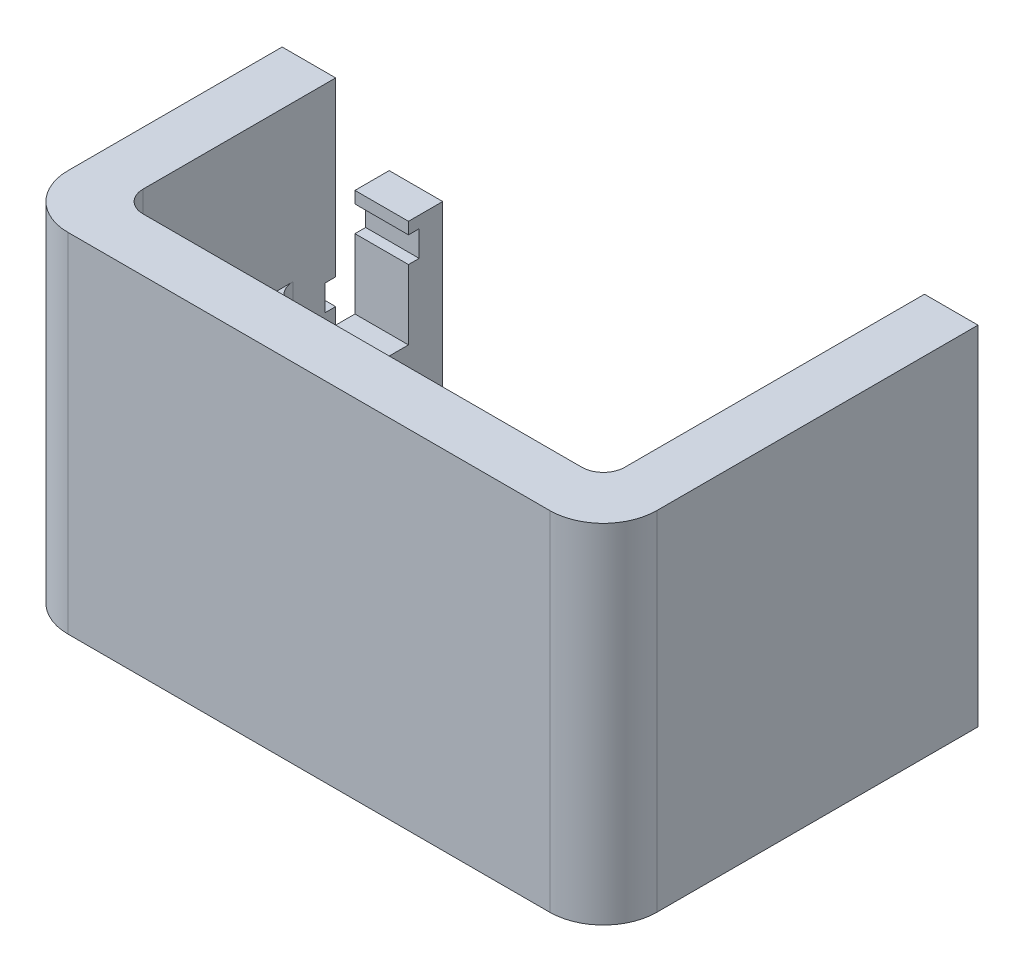
SolidWorks part; units mm, degrees
ref_plane "Front Plane" through (0, 0, 0) normal (0, 0, 1) x (1, 0, 0)
ref_plane "Top Plane" through (0, 0, 0) normal (0, 1, 0) x (1, 0, 0)
ref_plane "Right Plane" through (0, 0, 0) normal (1, 0, 0) x (0, 0, -1)
sketch "Sketch1" plane through (0, 0, 0) normal (0, 1, 0) x (1, 0, 0)
  line L0 (0, -55) -> (0, 55) construction
  line L1 (-34.925, -15.875) -> (34.925, -15.875)
  line L2 (-34.925, -15.875) -> (-34.925, 15.875)
  line L3 (-34.925, 15.875) -> (34.925, 15.875) construction
  line L4 (34.925, -15.875) -> (34.925, 15.875)
  line L5 (-34.925, -15.875) -> (34.925, 15.875) construction
  line L6 (-34.925, 15.875) -> (34.925, -15.875) construction
  line L7 (28.575, 15.875) -> (-28.575, 15.875) construction
  line L8 (28.575, 15.875) -> (28.575, -9.525)
  line L9 (28.575, -9.525) -> (-28.575, -9.525)
  line L10 (-28.575, 15.875) -> (-28.575, -9.525)
  line L11 (28.575, 15.875) -> (-28.575, -9.525) construction
  line L12 (28.575, -9.525) -> (-28.575, 15.875) construction
  line L13 (-28.575, 15.875) -> (-34.925, 15.875)
  line L14 (34.925, 15.875) -> (34.925, 28.575)
  line L15 (34.925, 28.575) -> (28.575, 28.575)
  line L16 (28.575, 28.575) -> (28.575, 15.875)
  point P0 (0, 0)
  point P6 (0, 3.175)
  point P11 (0, -9.525)
  dimension "D1" = 31.75
  dimension "D2" = 69.85
  dimension "D3" = 57.15
  dimension "D4" = 25.4
  dimension "D5" = 44.45
extrude "Boss-Extrude1" add sketch "Sketch1" along normal blind 38.1 contours L10 L3 L2 L1 L4 L8 L9
sketch "Sketch5" plane through (-28.575, 0, 0) normal (1, 0, 0) x (0, 0, -1)
  line L0 (15.875, 0) -> (-9.525, 0) construction
  line L1 (0.635, 16.51) -> (8.255, 16.51)
  line L2 (0.635, 16.51) -> (0.635, 19.685)
  line L3 (0.635, 19.685) -> (8.255, 19.685)
  line L4 (8.255, 16.51) -> (8.255, 19.685)
  line L5 (0.635, 16.51) -> (8.255, 19.685) construction
  line L6 (0.635, 19.685) -> (8.255, 16.51) construction
  line L10 (15.875, 38.1) -> (15.875, 0) construction
  point P0 (4.445, 18.0975)
  dimension "D1" = 7.62
  dimension "D2" = 3.175
  dimension "D3" = 16.51
  dimension "D4" = 7.62
extrude "Boss-Extrude2" add sketch "Sketch5" along normal blind 10.16 contours L3 L4 L1 L2
sketch "Sketch7" plane through (0, 19.685, 0) normal (0, 1, 0) x (1, 0, 0)
  line L1 (-28.575, 0.635) -> (-28.575, 8.255) construction
  line L3 (-18.415, 0.635) -> (-28.575, 0.635) construction
  point P0 (-23.241, 4.445)
  dimension "D1" = 3.81
  dimension "D2" = 5.334
hole_wizard "#6 Clearance Hole1" positions "Sketch8" profile "Sketch10" hole size "#6" standard "ANSI Inch" end condition up to next
sketch "Sketch8" plane through (0, 19.685, 0) normal (0, 1, 0) x (1, 0, 0)
  point P0 (-23.241, 4.445)
sketch "Sketch10" plane through (-23.241, 19.685, -4.445) normal (1, 0, 0) x (0, 0, 1)
  line L0 (0, 0) -> (0, 3.175)
  line L1 (0, 3.175) -> (1.8986, 3.175)
  line L2 (1.8986, 3.175) -> (1.8986, 0)
  line L5 (1.8986, 0) -> (0, 0)
  line L11 (0, -6.35) -> (0, 107.95) construction
  dimension "Thru Hole Dia." = 3.7973
  dimension "Thru Hole Depth" = 3.175
mirror "Mirror4" about plane through (0, 0, 0) normal (1, 0, 0) of "#6 Clearance Hole1", "Boss-Extrude2"
sketch "Sketch11" plane through (0, 0, 0) normal (0, -1, 0) x (1, 0, 0)
  line L5 (-28.575, -15.875) -> (-28.575, 9.525) construction
  line L7 (-34.925, 15.875) -> (-34.925, -15.875) construction
  line L13 (-28.575, -28.575) -> (-28.575, 9.525)
  line L15 (-34.925, 15.875) -> (-34.925, -28.575)
  line L17 (-34.925, -28.575) -> (-28.575, -28.575)
  line L18 (-28.575, -15.875) -> (-34.925, -15.875) construction
  line L19 (-28.575, 9.525) -> (28.575, 9.525)
  line L20 (28.575, 9.525) -> (28.575, -28.575)
  line L21 (28.575, -28.575) -> (34.925, -28.575)
  line L22 (34.925, -28.575) -> (34.925, 15.875)
  line L23 (34.925, 15.875) -> (-34.925, 15.875)
  dimension "D1" = 12.7
extrude "Boss-Extrude3" add sketch "Sketch11" along normal blind 3.175 contours L15 L17 L13 L19 L20 L21 L22 L23
sketch "Sketch12" [suppressed] plane through (0, 0, 0) normal (0, 1, 0) x (1, 0, 0)
  line L0 (-28.575, 28.575) -> (-28.575, 15.875) construction
  line L1 (-34.925, 28.575) -> (-28.575, 28.575)
  line L2 (-34.925, 28.575) -> (-34.925, 24.511)
  line L3 (-34.925, 24.511) -> (-28.575, 24.511)
  line L4 (-28.575, 28.575) -> (-28.575, 24.511)
  dimension "D1" = 4.064
extrude "Boss-Extrude4" [suppressed] add sketch "Sketch12" along normal blind 12.7
fillet "Fillet1" radius 6.35 2 edges at (34.925, 17.4625, 15.875) (-34.925, 17.4625, 15.875)
fillet "Fillet2" radius 2.54 4 edges at (-28.575, 18.0975, -0.635) (-28.575, 18.0975, -8.255) (28.575, 18.0975, -0.635) (28.575, 18.0975, -8.255)
fillet "Fillet3" radius 2.54 2 edges at (-28.575, 16.51, -4.445) (28.575, 16.51, -4.445)
fillet "Fillet4" radius 2.54 2 edges at (-28.575, 17.4625, 9.525) (28.575, 17.4625, 9.525)
sketch "Sketch13" [suppressed] plane through (0, 38.1, 0) normal (0, 1, 0) x (1, 0, 0)
  line L0 (28.575, 28.575) -> (28.575, -6.985) construction
  line L1 (34.925, 28.575) -> (28.575, 28.575) construction
  line L2 (26.035, -9.525) -> (-26.035, -9.525) construction
  line L3 (29.845, -11.43) -> (-29.845, -11.43) construction
  line L4 (0, -55) -> (0, 55) construction
  line L5 (-28.575, 28.575) -> (-34.925, 28.575) construction
  line L6 (-28.575, 15.875) -> (-34.925, 15.875) construction
  point P0 (29.845, -11.43)
  point P1 (-29.845, -11.43)
  point P2 (0, -11.43)
  point P7 (31.75, 24.765)
  point P12 (-31.75, 12.065)
  point P15 (31.75, 28.575)
  point P18 (-31.75, 28.575)
  dimension "D1" = 1.27
  dimension "D2" = 3.81
  dimension "D3" = 1.905
  dimension "D4" = 3.81
hole_wizard "#6-40 Tapped Hole1" [suppressed] positions "Sketch14" profile "Sketch16" tap size "#6-40" standard "ANSI Inch"
sketch "Sketch14" [suppressed] plane through (0, 38.1, 0) normal (0, 1, 0) x (1, 0, 0)
  point P0 (29.845, -11.43)
  point P3 (-29.845, -11.43)
  point P6 (31.75, 24.765)
  point P9 (-31.75, 12.065)
cosmetic thread "Hole Thread1" [suppressed] parameters "D1"=35.052, "D2"=3.5052
cosmetic thread "Hole Thread2" [suppressed] parameters "D1"=35.052, "D2"=3.5052
sketch "Sketch16" plane through (29.845, 38.1, 11.43) normal (1, 0, 0) x (0, 0, 1)
  line L0 (0, 0) -> (0, 38.9623)
  line L1 (0, 38.9623) -> (1.4351, 38.1)
  line L2 (1.4351, 38.1) -> (1.4351, 0)
  line L5 (1.4351, 0) -> (0, 0)
  line L10 (0, 38.9623) -> (-1.4351, 38.1) construction
  line L11 (0, -6.35) -> (0, 107.95) construction
  dimension "Tap Drill Dia." = 2.8702
  dimension "Tap Drill Depth" = 38.1
  dimension "Drill Angle" = 118
cosmetic thread "Hole Thread3" [suppressed] parameters "D1"=35.052, "D2"=3.5052
cosmetic thread "Hole Thread4" [suppressed] parameters "D1"=35.052, "D2"=3.5052
sketch "Sketch17" [suppressed] plane through (-34.925, 0, 0) normal (-1, 0, 0) x (0, 0, 1)
  line L0 (-28.575, 0) -> (-28.575, 31.75)
  line L1 (-28.575, 31.75) -> (-15.875, 31.75)
  line L2 (24.4475, 0) -> (-24.4475, 0) construction
  line L3 (-28.575, 0) -> (-24.511, 0)
  line L4 (-24.511, 0) -> (-24.511, 27.686)
  line L5 (-24.511, 27.686) -> (-15.875, 27.686)
  line L6 (-15.875, 31.75) -> (-15.875, 0) construction
  line L7 (-15.875, 27.686) -> (-15.875, 31.75)
  dimension "D1" = 4.064
  dimension "D2" = 4.064
extrude "Boss-Extrude5" [suppressed] add sketch "Sketch17" against normal up to surface (6.35 mm away)
sketch "Sketch18" plane through (-34.925, 0, 0) normal (-1, 0, 0) x (0, 0, 1)
  line L0 (-24.511, 19.05) -> (-28.575, 19.05)
  line L1 (-28.575, 38.1) -> (-28.575, -3.175) construction
  line L2 (-28.575, 19.05) -> (-24.511, 19.05) construction
  line L3 (-28.575, 19.05) -> (-28.575, 0)
  line L4 (-28.575, 0) -> (-15.875, 0)
  line L5 (-15.875, 0) -> (-15.875, 6.35)
  line L6 (-15.875, 38.1) -> (-15.875, 0) construction
  line L7 (-15.875, 6.35) -> (-24.511, 6.35)
  line L8 (-24.511, 22.7511) -> (-24.511, 6.858) construction
  line L9 (-24.511, 6.35) -> (-24.511, 19.05)
  dimension "D1" = 6.35
extrude "Boss-Extrude6" add sketch "Sketch18" against normal up to surface (6.35 mm away) up to face at (-28.575, 16.8275, -4.445)
sketch "Sketch19" plane through (-34.925, 0, 0) normal (-1, 0, 0) x (0, 0, 1)
  line L0 (-15.875, 14.605) -> (-17.145, 14.605) construction
  line L1 (-15.875, 17.653) -> (-14.605, 17.653)
  line L2 (-15.875, 17.653) -> (-15.875, 14.605)
  line L3 (-15.875, 14.605) -> (-14.605, 14.605)
  line L4 (-14.605, 17.653) -> (-14.605, 14.605)
  line L5 (-24.511, 17.653) -> (-25.781, 17.653)
  line L6 (-24.511, 17.653) -> (-24.511, 14.605)
  line L7 (-24.511, 14.605) -> (-25.781, 14.605)
  line L8 (-25.781, 17.653) -> (-25.781, 14.605)
  dimension "D1" = 1.27
extrude "Cut-Extrude1" cut sketch "Sketch19" against normal up to next
